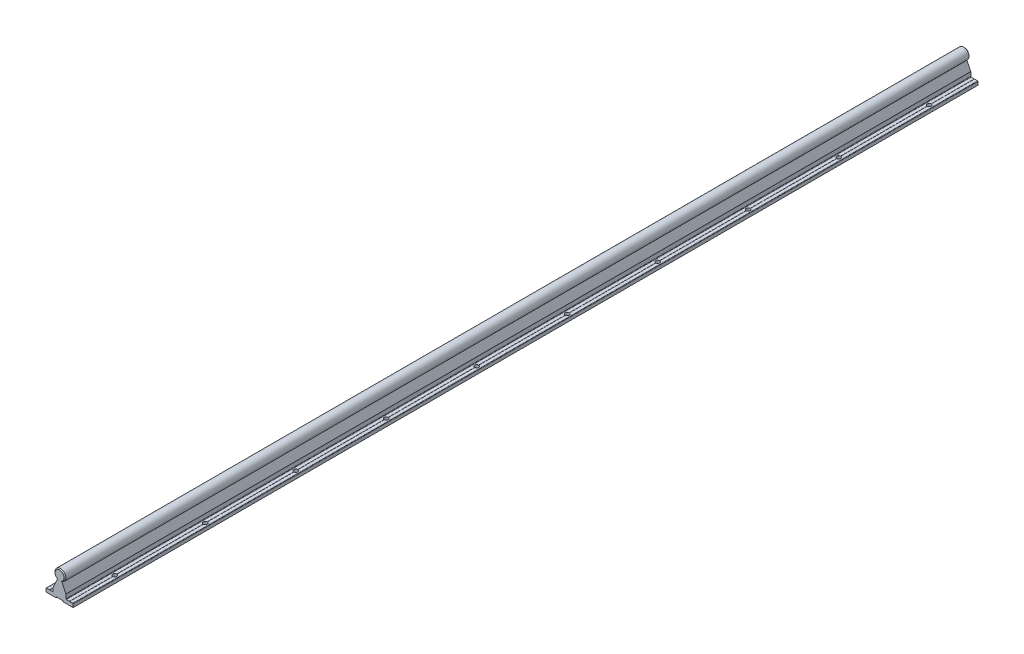
SolidWorks part; units mm, degrees
ref_plane "Plan de face" through (0, 0, 0) normal (0, 0, 1) x (1, 0, 0)
ref_plane "Plan de dessus" through (0, 0, 0) normal (0, 1, 0) x (1, 0, 0)
ref_plane "Plan de droite" through (0, 0, 0) normal (1, 0, 0) x (0, 0, -1)
sketch "Esquisse1" plane through (0, 0, 0) normal (0, 0, 1) x (1, 0, 0)
  line L0 (0, 0) -> (0, 3.5)
  line L1 (30, 0) -> (30, 4) construction
  line L2 (22.5, 4) -> (25.9, 4)
  line L3 (22, 4) -> (22, 9) construction
  line L4 (0, 0) -> (11, 0)
  line L5 (11, 0) -> (11, 0.5)
  line L6 (30, 0) -> (19, 0)
  line L7 (19, 0) -> (19, 0.5)
  line L8 (30, 0) -> (30, 3.5)
  line L9 (29.5, 4) -> (26.1, 4)
  line L10 (22, 4.5) -> (22, 8.8856)
  line L11 (11.5, 1) -> (18.5, 1)
  line L12 (0.5, 4) -> (3.9, 4)
  line L13 (8, 4.5) -> (8, 8.8856)
  line L14 (7.5, 4) -> (4.1, 4)
  line L15 (4.1, 4) -> (4.1, 3.8)
  line L16 (4.1, 3.8) -> (3.9, 3.8)
  line L17 (3.9, 3.8) -> (3.9, 4)
  line L18 (26.1, 4) -> (26.1, 3.8)
  line L19 (26.1, 3.8) -> (25.9, 3.8)
  line L20 (25.9, 3.8) -> (25.9, 4)
  line L23 (8.0497, 9.103) -> (12.3915, 18.0967)
  line L24 (21.9503, 9.103) -> (17.6085, 18.0967)
  arc A0 (0, 3.5) -> (0.5, 4) centre (0.5, 3.5) cw
  arc A1 (12.3915, 18.0967) -> (17.6085, 18.0967) centre (15, 23.5) cw
  arc A2 (29.5, 4) -> (30, 3.5) centre (29.5, 3.5) cw
  arc A3 (8, 4.5) -> (7.5, 4) centre (7.5, 4.5) cw
  arc A4 (22, 4.5) -> (22.5, 4) centre (22.5, 4.5) ccw
  arc A5 (18.5, 1) -> (19, 0.5) centre (18.5, 0.5) cw
  arc A6 (11.5, 1) -> (11, 0.5) centre (11.5, 0.5) ccw
  arc A7 (8.0497, 9.103) -> (8, 8.8856) centre (8.5, 8.8856) ccw
  arc A8 (22, 8.8856) -> (21.9503, 9.103) centre (21.5, 8.8856) ccw
  point P26 (0, 4)
  point P32 (8, 4)
  dimension "D1" = 0.5
  dimension "D2" = 0.5
  dimension "D3" = 0.5
  dimension "D4" = 0.5
  dimension "D5" = 0.5
  dimension "D6" = 0.5
  dimension "D7" = 0.5
  dimension "D8" = 0.5
extrude "Boss.-Extru.1" add sketch "Esquisse1" along normal blind 1000
chamfer "Chanfrein5" distance 1 angle 45 1 edges at (15, 29.5, 0)
chamfer "Chanfrein6" distance 1 angle 45 1 edges at (15, 29.5, 1000)
sketch "Esquisse2" plane through (0, 0, 0) normal (0, -1, 0) x (1, 0, 0)
  circle A2 centre (4, 850) radius 2.25
  circle A3 centre (26, 850) radius 2.25
  circle A4 centre (26, 950) radius 2.25
  circle A5 centre (4, 950) radius 2.25
extrude "Enlèv. mat.-Extru.1" cut sketch "Esquisse2" against normal up to next contours A2 | A3 | A4 | A5
pattern_linear "Répétition linéaire1" count 9 spacing 100 along (0, 0, -1) of "Enlèv. mat.-Extru.1"
